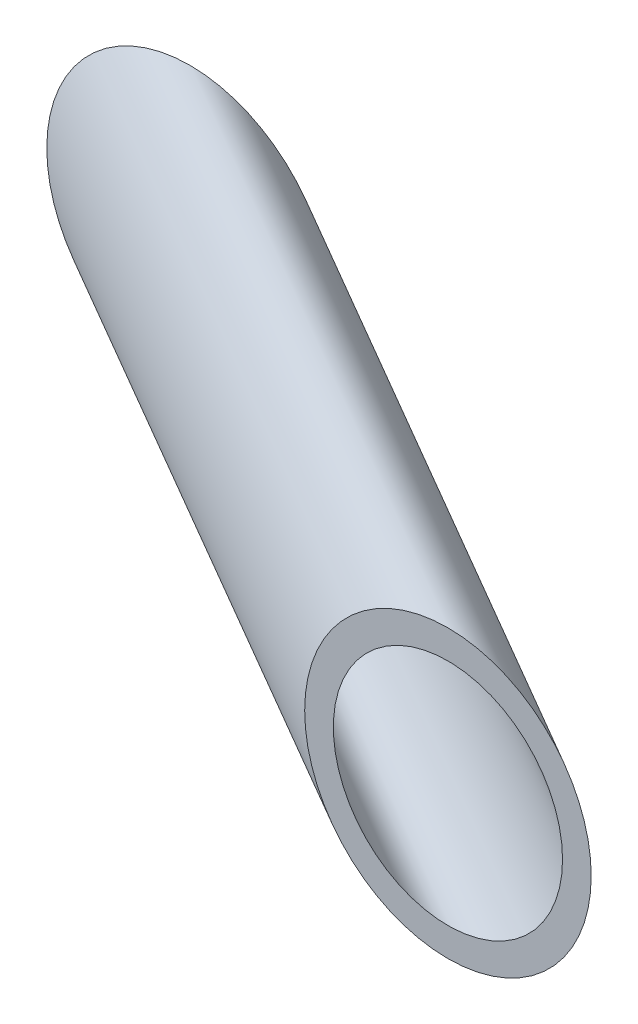
SolidWorks part; units mm, degrees
material "Copper"
ref_plane "Front Plane" through (0, 0, 0) normal (0, 0, 1) x (1, 0, 0)
ref_plane "Top Plane" through (0, 0, 0) normal (0, 1, 0) x (1, 0, 0)
ref_plane "Right Plane" through (0, 0, 0) normal (1, 0, 0) x (0, 0, -1)
sketch "Sketch1" plane through (0, 0, 0) normal (0, 0, 1) x (1, 0, 0)
  circle A0 centre (0, 0) radius 12.7
  circle A1 centre (0, 0) radius 10.16
  dimension "D1" = 20.32
  dimension "D2" = 25.4
sketch "Sketch2" plane through (0, 0, 0) normal (0, 1, 0) x (1, 0, 0)
  line L0 (0, 0) -> (54.61, -31.75)
  dimension "D1" = 31.75
  dimension "D2" = 54.61
sweep "Sweep1" add profiles "Sketch1" path "Sketch2"
